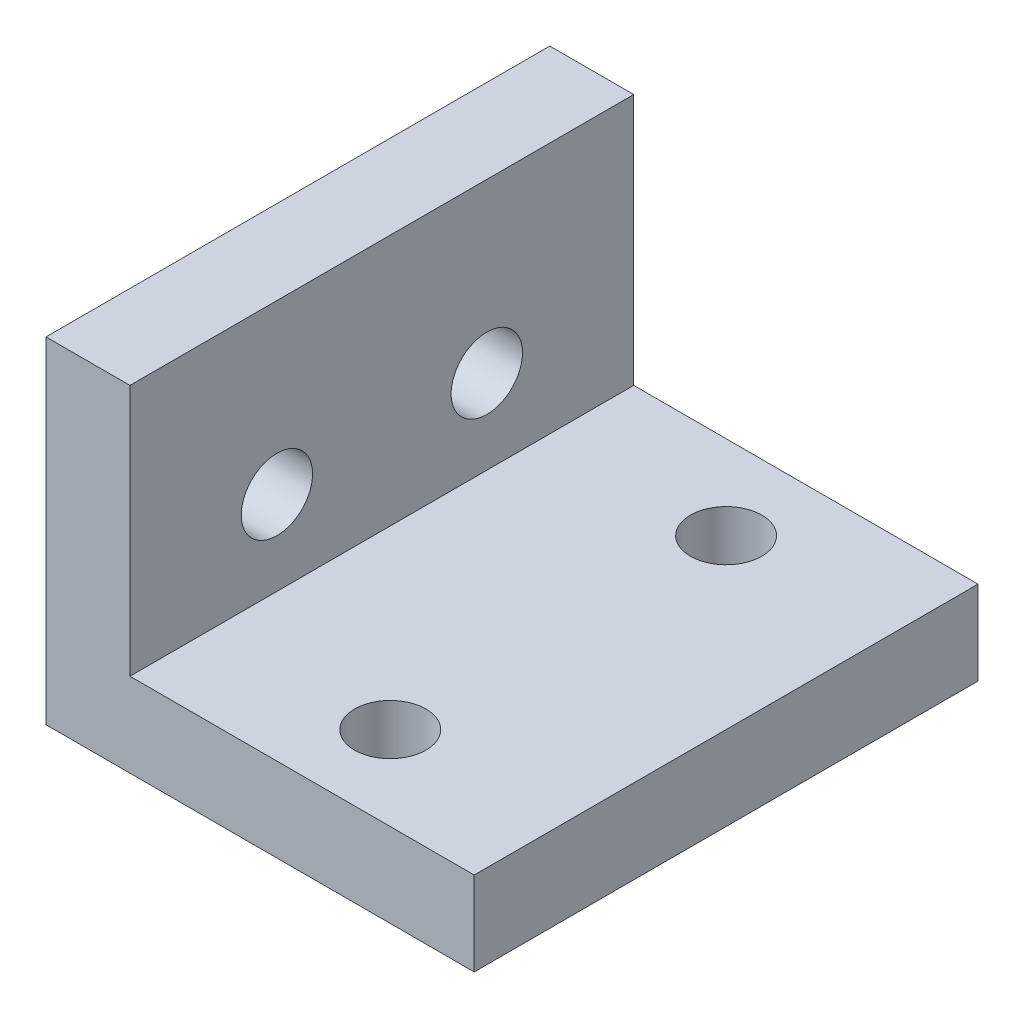
SolidWorks part; units mm, degrees
material "A6061"
ref_plane "前视基准面" through (0, 0, 0) normal (0, 0, 1) x (1, 0, 0)
ref_plane "上视基准面" through (0, 0, 0) normal (0, 1, 0) x (1, 0, 0)
ref_plane "右视基准面" through (0, 0, 0) normal (1, 0, 0) x (0, 0, -1)
sketch "草图1" plane through (0, 0, 0) normal (0, 0, 1) x (1, 0, 0)
  line L0 (0, 40) -> (0, 0)
  line L1 (0, 0) -> (51, 0)
  line L2 (51, 0) -> (51, 10)
  line L3 (51, 10) -> (10, 10)
  line L4 (10, 10) -> (10, 40)
  line L5 (10, 40) -> (0, 40)
  dimension "D1" = 10
  dimension "D2" = 10
  dimension "D3" = 40
  dimension "D4" = 51
extrude "凸台-拉伸1" add sketch "草图1" along normal blind 60
sketch "草图2" plane through (0, 10, 0) normal (0, 1, 0) x (1, 0, 0)
sketch "草图3" plane through (0, 10, 0) normal (0, 1, 0) x (1, 0, 0)
  line L0 (31, 4.4006) -> (31, -68.7068) construction
  line L1 (51, -60) -> (51, 0) construction
  line L2 (0, -30) -> (51, -30) construction
  line L3 (0, -60) -> (0, 0) construction
  circle A0 centre (31, -10) radius 3
  circle A1 centre (31, -30) radius 3
  circle A2 centre (31, -50) radius 3
  dimension "D2" = 6
  dimension "D3" = 40
  dimension "D1" = 20
sketch "草图4" plane through (10, 0, 0) normal (1, 0, 0) x (0, 0, -1)
  line L0 (-63.9435, 20) -> (8.2376, 20) construction
  line L1 (-30, 0) -> (-30, 43.2285) construction
  line L2 (-60, 0) -> (0, 0) construction
  line L3 (-60, 40) -> (0, 40) construction
  circle A0 centre (-17.5, 20) radius 3
  circle A1 centre (-30, 20) radius 3
  circle A2 centre (-42.5, 20) radius 3
  dimension "D1" = 6
  dimension "D3" = 25
  dimension "D2" = 20
hole_wizard "Ø8.5 (8.5) 直径孔1" positions "3D草图1" profile "草图5" hole size "Ø8.5" standard "GB" end condition through all
sketch3d "3D草图1"
  point P0 (10, 20, 42.5)
  point P6 (10, 20, 17.5)
  point P9 (31, 10, 50)
  point P15 (31, 10, 10)
sketch "草图5" plane through (10, 20, 42.5) normal (0, 1, 0) x (0, 0, -1)
  line L0 (0, 0) -> (0, 10)
  line L1 (0, 10) -> (4.25, 10)
  line L2 (4.25, 10) -> (4.25, 0)
  line L5 (4.25, 0) -> (0, 0)
  line L11 (0, -6.35) -> (0, 107.95) construction
  dimension "通孔孔直径" = 8.5
  dimension "通孔孔深度" = 10
